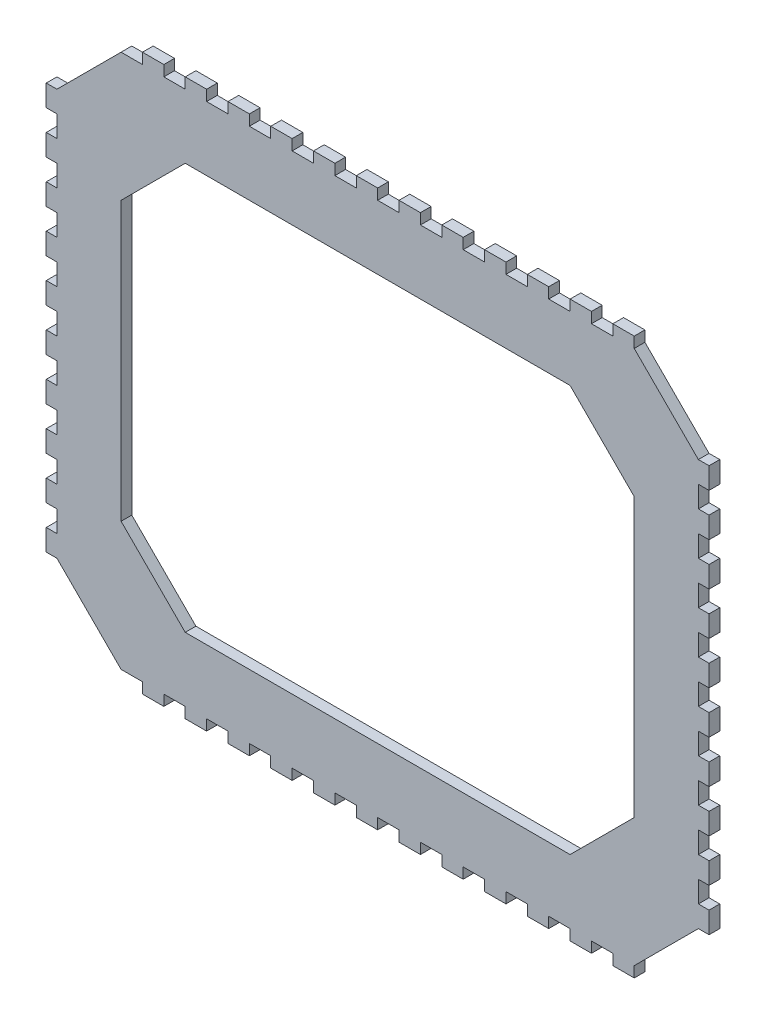
SolidWorks part; units mm, degrees
material "Buche"
ref_plane "Ebene vorne" through (0, 0, 0) normal (0, 0, 1) x (1, 0, 0)
ref_plane "Ebene oben" through (0, 0, 0) normal (0, 1, 0) x (1, 0, 0)
ref_plane "Ebene rechts" through (0, 0, 0) normal (1, 0, 0) x (0, 0, -1)
sketch "Skizze1" plane through (0, 0, 0) normal (0, 0, 1) x (1, 0, 0)
  line L0 (30, 0) -> (0, 30)
  line L1 (50, 0) -> (60, 0)
  line L2 (0, 50) -> (-5, 50)
  line L3 (30, 250) -> (40, 250)
  line L4 (300, 30) -> (305, 30)
  line L5 (270, 0) -> (300, 30)
  line L6 (0, 220) -> (30, 250)
  line L7 (300, 220) -> (270, 250)
  line L8 (30, 190) -> (60, 220)
  line L9 (60, 30) -> (240, 30)
  line L10 (30, 60) -> (30, 190)
  line L11 (60, 220) -> (240, 220)
  line L12 (270, 60) -> (270, 190)
  line L13 (270, 190) -> (240, 220)
  line L14 (240, 30) -> (270, 60)
  line L15 (60, 30) -> (30, 60)
  line L16 (30, 0) -> (40, 0)
  line L17 (40, 0) -> (40, -5)
  line L18 (40, -5) -> (50, -5)
  line L19 (50, -5) -> (50, 0)
  line L20 (60, 0) -> (60, -5)
  line L21 (60, -5) -> (70, -5)
  line L22 (70, -5) -> (70, 0)
  line L23 (70, 0) -> (80, 0)
  line L24 (80, 0) -> (80, -5)
  line L25 (80, -5) -> (90, -5)
  line L26 (90, -5) -> (90, 0)
  line L27 (90, 0) -> (100, 0)
  line L28 (100, 0) -> (100, -5)
  line L29 (100, -5) -> (110, -5)
  line L30 (110, -5) -> (110, 0)
  line L31 (110, 0) -> (120, 0)
  line L32 (120, 0) -> (120, -5)
  line L33 (120, -5) -> (130, -5)
  line L34 (130, -5) -> (130, 0)
  line L35 (130, 0) -> (140, 0)
  line L36 (140, 0) -> (140, -5)
  line L37 (140, -5) -> (150, -5)
  line L38 (150, -5) -> (150, 0)
  line L39 (150, 0) -> (160, 0)
  line L40 (160, 0) -> (160, -5)
  line L41 (160, -5) -> (170, -5)
  line L42 (170, -5) -> (170, 0)
  line L43 (170, 0) -> (180, 0)
  line L44 (180, 0) -> (180, -5)
  line L45 (180, -5) -> (190, -5)
  line L46 (190, -5) -> (190, 0)
  line L47 (190, 0) -> (200, 0)
  line L48 (200, 0) -> (200, -5)
  line L49 (200, -5) -> (210, -5)
  line L50 (210, -5) -> (210, 0)
  line L51 (210, 0) -> (220, 0)
  line L52 (220, 0) -> (220, -5)
  line L53 (220, -5) -> (230, -5)
  line L54 (230, -5) -> (230, 0)
  line L55 (230, 0) -> (240, 0)
  line L56 (240, 0) -> (240, -5)
  line L57 (240, -5) -> (250, -5)
  line L58 (250, -5) -> (250, 0)
  line L59 (250, 0) -> (260, 0)
  line L60 (260, 0) -> (260, -5)
  line L61 (260, -5) -> (270, -5)
  line L62 (270, -5) -> (270, 0)
  line L63 (0, 30) -> (-5, 30)
  line L64 (-5, 30) -> (-5, 40)
  line L65 (-5, 40) -> (0, 40)
  line L66 (0, 40) -> (0, 50)
  line L67 (-5, 50) -> (-5, 60)
  line L68 (-5, 60) -> (0, 60)
  line L69 (0, 60) -> (0, 70)
  line L70 (0, 70) -> (-5, 70)
  line L71 (-5, 70) -> (-5, 80)
  line L72 (-5, 80) -> (0, 80)
  line L73 (0, 80) -> (0, 90)
  line L74 (0, 90) -> (-5, 90)
  line L75 (-5, 90) -> (-5, 100)
  line L76 (-5, 100) -> (0, 100)
  line L77 (0, 100) -> (0, 110)
  line L78 (0, 110) -> (-5, 110)
  line L79 (-5, 110) -> (-5, 120)
  line L80 (-5, 120) -> (0, 120)
  line L81 (0, 120) -> (0, 130)
  line L82 (0, 130) -> (-5, 130)
  line L83 (-5, 130) -> (-5, 140)
  line L84 (-5, 140) -> (0, 140)
  line L85 (0, 140) -> (0, 150)
  line L86 (0, 150) -> (-5, 150)
  line L87 (-5, 150) -> (-5, 160)
  line L88 (-5, 160) -> (0, 160)
  line L89 (0, 160) -> (0, 170)
  line L90 (0, 170) -> (-5, 170)
  line L91 (-5, 170) -> (-5, 180)
  line L92 (-5, 180) -> (0, 180)
  line L93 (0, 180) -> (0, 190)
  line L94 (0, 190) -> (-5, 190)
  line L95 (-5, 190) -> (-5, 200)
  line L96 (-5, 200) -> (0, 200)
  line L97 (0, 200) -> (0, 210)
  line L98 (0, 210) -> (-5, 210)
  line L99 (-5, 210) -> (-5, 220)
  line L100 (-5, 220) -> (0, 220)
  line L101 (305, 30) -> (305, 40)
  line L102 (0, 220) -> (0, 230) [skipped]
  line L103 (305, 40) -> (300, 40)
  line L104 (300, 40) -> (300, 50)
  line L105 (300, 50) -> (305, 50)
  line L106 (305, 50) -> (305, 60)
  line L107 (305, 60) -> (300, 60)
  line L108 (300, 60) -> (300, 70)
  line L109 (300, 70) -> (305, 70)
  line L110 (305, 70) -> (305, 80)
  line L111 (305, 80) -> (300, 80)
  line L112 (300, 80) -> (300, 90)
  line L113 (300, 90) -> (305, 90)
  line L114 (305, 90) -> (305, 100)
  line L115 (305, 100) -> (300, 100)
  line L116 (300, 100) -> (300, 110)
  line L117 (300, 110) -> (305, 110)
  line L118 (305, 110) -> (305, 120)
  line L119 (305, 120) -> (300, 120)
  line L120 (300, 120) -> (300, 130)
  line L121 (300, 130) -> (305, 130)
  line L122 (305, 130) -> (305, 140)
  line L123 (305, 140) -> (300, 140)
  line L124 (300, 140) -> (300, 150)
  line L125 (300, 150) -> (305, 150)
  line L126 (305, 150) -> (305, 160)
  line L127 (305, 160) -> (300, 160)
  line L128 (300, 160) -> (300, 170)
  line L129 (300, 170) -> (305, 170)
  line L130 (305, 170) -> (305, 180)
  line L131 (305, 180) -> (300, 180)
  line L132 (300, 180) -> (300, 190)
  line L133 (300, 190) -> (305, 190)
  line L134 (305, 190) -> (305, 200)
  line L135 (305, 200) -> (300, 200)
  line L136 (300, 200) -> (300, 210)
  line L137 (300, 210) -> (305, 210)
  line L138 (305, 210) -> (305, 220)
  line L139 (305, 220) -> (300, 220)
  line L140 (40, 250) -> (40, 255)
  line L141 (300, 220) -> (300, 230) [skipped]
  line L142 (40, 255) -> (50, 255)
  line L143 (50, 255) -> (50, 250)
  line L144 (50, 250) -> (60, 250)
  line L145 (60, 250) -> (60, 255)
  line L146 (60, 255) -> (70, 255)
  line L147 (70, 255) -> (70, 250)
  line L148 (70, 250) -> (80, 250)
  line L149 (80, 250) -> (80, 255)
  line L150 (80, 255) -> (90, 255)
  line L151 (90, 255) -> (90, 250)
  line L152 (90, 250) -> (100, 250)
  line L153 (100, 250) -> (100, 255)
  line L154 (100, 255) -> (110, 255)
  line L155 (110, 255) -> (110, 250)
  line L156 (110, 250) -> (120, 250)
  line L157 (120, 250) -> (120, 255)
  line L158 (120, 255) -> (130, 255)
  line L159 (130, 255) -> (130, 250)
  line L160 (130, 250) -> (140, 250)
  line L161 (140, 250) -> (140, 255)
  line L162 (140, 255) -> (150, 255)
  line L163 (150, 255) -> (150, 250)
  line L164 (150, 250) -> (160, 250)
  line L165 (160, 250) -> (160, 255)
  line L166 (160, 255) -> (170, 255)
  line L167 (170, 255) -> (170, 250)
  line L168 (170, 250) -> (180, 250)
  line L169 (180, 250) -> (180, 255)
  line L170 (180, 255) -> (190, 255)
  line L171 (190, 255) -> (190, 250)
  line L172 (190, 250) -> (200, 250)
  line L173 (200, 250) -> (200, 255)
  line L174 (200, 255) -> (210, 255)
  line L175 (210, 255) -> (210, 250)
  line L176 (210, 250) -> (220, 250)
  line L177 (220, 250) -> (220, 255)
  line L178 (220, 255) -> (230, 255)
  line L179 (230, 255) -> (230, 250)
  line L180 (230, 250) -> (240, 250)
  line L181 (240, 250) -> (240, 255)
  line L182 (240, 255) -> (250, 255)
  line L183 (250, 255) -> (250, 250)
  line L184 (250, 250) -> (260, 250)
  line L185 (260, 250) -> (260, 255)
  line L186 (260, 255) -> (270, 255)
  line L187 (270, 255) -> (270, 250)
  dimension "D1" = 12
  dimension "D2" = 10
  dimension "D3" = 10
  dimension "D4" = 12
extrude "Aufsatz-Linear austragen1" add sketch "Skizze1" along normal blind 5
